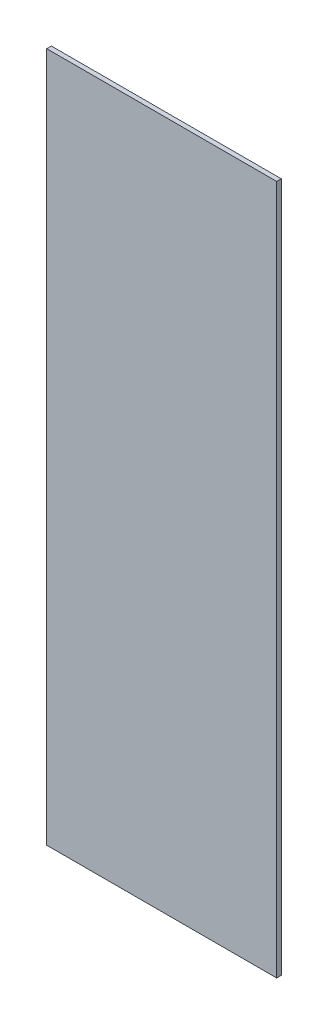
SolidWorks part; units mm, degrees
ref_plane "Front Plane" through (0, 0, 0) normal (0, 0, 1) x (1, 0, 0)
ref_plane "Top Plane" through (0, 0, 0) normal (0, 1, 0) x (1, 0, 0)
ref_plane "Right Plane" through (0, 0, 0) normal (1, 0, 0) x (0, 0, -1)
sketch "Sketch1" plane through (0, 0, 0) normal (0, 0, 1) x (1, 0, 0)
  line L1 (50, -150) -> (-50, -150)
  line L2 (50, -150) -> (50, 150)
  line L3 (50, 150) -> (-50, 150)
  line L4 (-50, -150) -> (-50, 150)
  line L5 (50, -150) -> (-50, 150) construction
  line L6 (50, 150) -> (-50, -150) construction
  point P0 (0, 0)
  dimension "D1" = 100
  dimension "D2" = 300
extrude "Boss-Extrude1" add sketch "Sketch1" along normal blind 2
sketch "Sketch2" plane through (0, 0, 2) normal (0, 0, 1) x (1, 0, 0)
  line L0 (-50, 150) -> (-50, -150) construction
  line L1 (50, 150) -> (-50, 150) construction
  line L2 (-50, -150) -> (50, -150) construction
  line L4 (0, -55) -> (0, 55) construction
  circle A0 centre (-45, 122) radius 1.5
  circle A1 centre (-45, 77) radius 1.5
  circle A2 centre (45, 122) radius 1.5
  circle A3 centre (45, 77) radius 1.5
  circle A4 centre (-45, 24) radius 1.5
  circle A5 centre (-45, -21) radius 1.5
  circle A6 centre (45, 24) radius 1.5
  circle A7 centre (45, -21) radius 1.5
  circle A8 centre (-45, -74) radius 1.5
  circle A9 centre (-45, -119) radius 1.5
  circle A10 centre (45, -74) radius 1.5
  circle A11 centre (45, -119) radius 1.5
  circle A13 centre (16.5, -147) radius 1.5
  circle A14 centre (-16.5, -147) radius 1.5
  circle A15 centre (-16.5, -49) radius 1.5
  circle A16 centre (16.5, -49) radius 1.5
  circle A17 centre (-16.5, 49) radius 1.5
  circle A18 centre (16.5, 49) radius 1.5
  circle A19 centre (-16.5, 147) radius 1.5
  circle A20 centre (16.5, 147) radius 1.5
  dimension "D1" = 3
  dimension "D3" = 28
  dimension "D4" = 3
  dimension "D6" = 5
  dimension "D10" = 3
  dimension "D11" = 33
  dimension "D13" = 3
  dimension "D2" = 5
  dimension "D5" = 45
  dimension "D9" = 31
  dimension "D7" = 2
  dimension "D8" = 3
  dimension "D12" = 4
